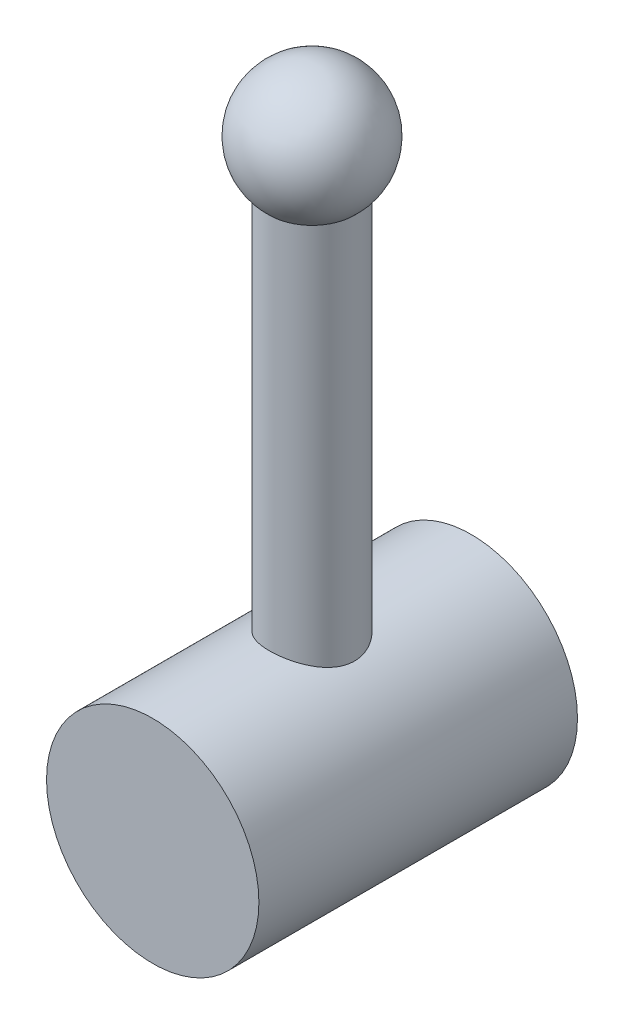
SolidWorks part; units mm, degrees
ref_plane "前视基准面" through (0, 0, 0) normal (0, 0, 1) x (1, 0, 0)
ref_plane "上视基准面" through (0, 0, 0) normal (0, 1, 0) x (1, 0, 0)
ref_plane "右视基准面" through (0, 0, 0) normal (1, 0, 0) x (0, 0, -1)
other "Configuration Table"
sketch "草图1" plane through (0, 0, 0) normal (0, 0, 1) x (1, 0, 0)
  circle A1 centre (0, 0) radius 10
  point P1 (0, 0)
  point P4 (0, 0)
extrude "凸台-拉伸2" add sketch "草图1" along normal blind 30
sketch "草图2" plane through (0, 0, 0) normal (0, 1, 0) x (1, 0, 0)
  line L0 (0, 0) -> (0, -30) construction
  line L1 (-10, -30) -> (10, -30) construction
  circle A0 centre (0, -15) radius 4
extrude "凸台-拉伸3" add sketch "草图2" along normal blind 50
ref_plane "基准面1" through (0, 50, 0) normal (0, 1, 0) x (1, 0, 0)
sketch "草图3" plane through (0, 50, 0) normal (0, 1, 0) x (1, 0, 0)
  line L0 (0, -9) -> (0, -21)
  arc A0 (0, -21) -> (0, -9) centre (0, -15) ccw
revolve "旋转1" add sketch "草图3" angle 360 about L0
